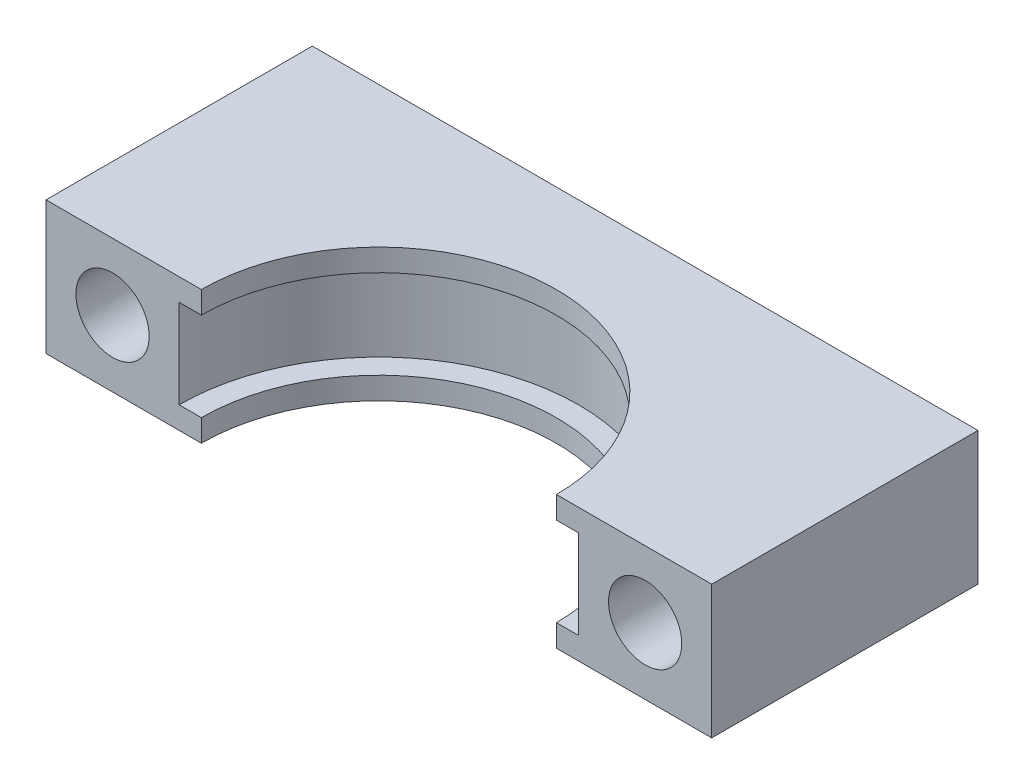
SolidWorks part; units mm, degrees
ref_plane "前视基准面" through (0, 0, 0) normal (0, 0, 1) x (1, 0, 0)
ref_plane "上视基准面" through (0, 0, 0) normal (0, 1, 0) x (1, 0, 0)
ref_plane "右视基准面" through (0, 0, 0) normal (1, 0, 0) x (0, 0, -1)
sketch "草图1" plane through (0, 0, 0) normal (0, 1, 0) x (1, 0, 0)
  line L0 (0, 0) -> (0, 6) construction
  line L1 (-15, 12) -> (15, 12)
  line L2 (-15, 12) -> (-15, 0)
  line L3 (-15, 0) -> (15, 0)
  line L4 (15, 12) -> (15, 0)
  line L5 (-15, 12) -> (15, 0) construction
  line L6 (-15, 0) -> (15, 12) construction
  point P0 (0, 6)
  dimension "D1" = 30
  dimension "D2" = 12
extrude "凸台-拉伸1" add sketch "草图1" along normal blind 6
sketch "草图2" plane through (0, 0, 0) normal (0, 0, 1) x (1, 0, 0)
  line L0 (0, 0) -> (0, 6)
  line L1 (-15, 6) -> (15, 6) construction
  line L2 (0, 6) -> (-8, 6)
  line L3 (-8, 6) -> (-8, 5)
  line L4 (-8, 5) -> (-9, 5)
  line L5 (-9, 5) -> (-9, 1)
  line L6 (-9, 1) -> (-8, 1)
  line L7 (-8, 1) -> (-8, 0)
  line L8 (-15, 0) -> (15, 0) construction
  line L9 (-8, 0) -> (0, 0)
  line L10 (-9, 3) -> (0, 3) construction
  dimension "D1" = 8
  dimension "D2" = 4
  dimension "D3" = 9
revolve "切除-旋转1" cut sketch "草图2" angle 360 about L0
sketch "草图4" plane through (0, 0, -12) normal (0, 0, -1) x (-1, 0, 0)
  line L0 (-15, 3) -> (-12, 3) construction
  line L1 (-15, 6) -> (-15, 0) construction
  line L2 (-12, 3) -> (-15, 6) construction
  line L3 (-15, 6) -> (15, 6) construction
  circle A0 centre (-12, 3) radius 1.65
  dimension "D1" = 3.3
  dimension "D2" = 45
extrude "切除-拉伸2" cut sketch "草图4" against normal up to next
mirror "镜向1" about plane through (0, 0, 0) normal (1, 0, 0) of "切除-拉伸2"
